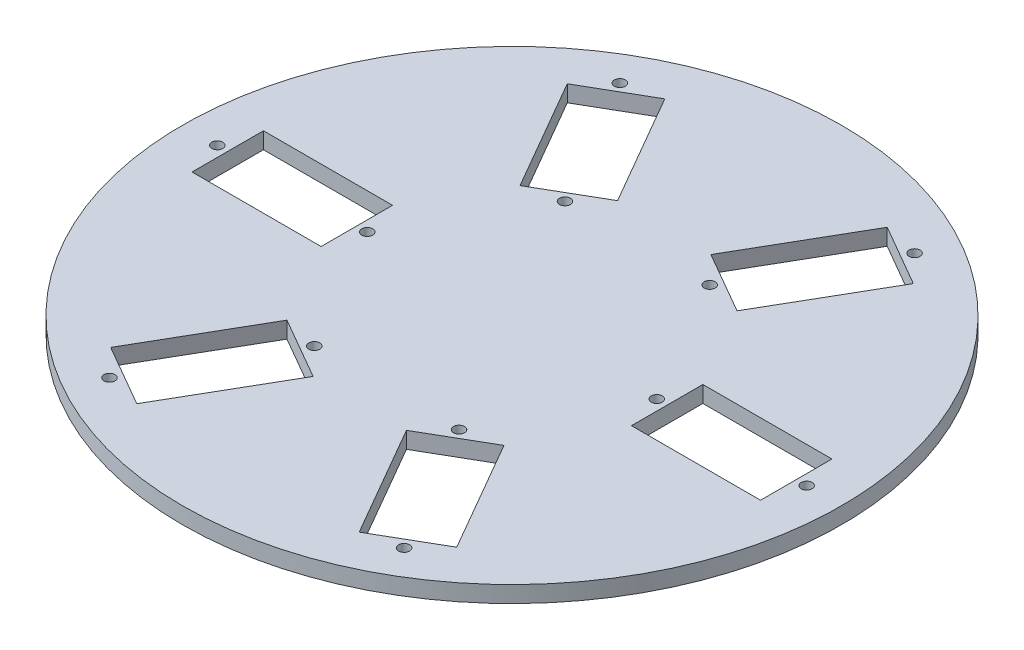
SolidWorks part; units mm, degrees
ref_plane "Спереди" through (0, 0, 0) normal (0, 0, 1) x (1, 0, 0)
ref_plane "Сверху" through (0, 0, 0) normal (0, 1, 0) x (1, 0, 0)
ref_plane "Справа" through (0, 0, 0) normal (1, 0, 0) x (0, 0, -1)
sketch "Sketch1" plane through (0, 0, 0) normal (0, 1, 0) x (1, 0, 0)
  line L0 (-60, 0) -> (60, 0) construction
  line L1 (28.25, -6.5) -> (28.25, 6.5)
  line L2 (28.25, 6.5) -> (51.75, 6.5)
  line L3 (51.75, 6.5) -> (51.75, -6.5)
  line L4 (28.25, -6.5) -> (51.75, -6.5)
  line L5 (40, -6.5) -> (40, 6.5) construction
  line L6 (0, 60) -> (0, -60) construction
  line L7 (28.25, 6.5) -> (28.25, -6.5)
  line L8 (51.75, -6.5) -> (51.75, 6.5)
  line L9 (8.4958, -27.7152) -> (19.7542, -21.2152)
  line L10 (19.7542, -21.2152) -> (31.5042, -41.5668)
  line L11 (31.5042, -41.5668) -> (20.2458, -48.0668)
  line L12 (8.4958, -27.7152) -> (20.2458, -48.0668)
  line L13 (19.7542, -21.2152) -> (8.4958, -27.7152)
  line L14 (20.2458, -48.0668) -> (31.5042, -41.5668)
  line L15 (14.3708, -37.891) -> (25.6292, -31.391) construction
  line L16 (-19.7542, -21.2152) -> (-8.4958, -27.7152)
  line L17 (-8.4958, -27.7152) -> (-20.2458, -48.0668)
  line L18 (-20.2458, -48.0668) -> (-31.5042, -41.5668)
  line L19 (-19.7542, -21.2152) -> (-31.5042, -41.5668)
  line L20 (-8.4958, -27.7152) -> (-19.7542, -21.2152)
  line L21 (-31.5042, -41.5668) -> (-20.2458, -48.0668)
  line L22 (-25.6292, -31.391) -> (-14.3708, -37.891) construction
  line L23 (-28.25, 6.5) -> (-28.25, -6.5)
  line L24 (-28.25, -6.5) -> (-51.75, -6.5)
  line L25 (-51.75, -6.5) -> (-51.75, 6.5)
  line L26 (-28.25, 6.5) -> (-51.75, 6.5)
  line L27 (-28.25, -6.5) -> (-28.25, 6.5)
  line L28 (-51.75, 6.5) -> (-51.75, -6.5)
  line L29 (-40, 6.5) -> (-40, -6.5) construction
  line L30 (-8.4958, 27.7152) -> (-19.7542, 21.2152)
  line L31 (-19.7542, 21.2152) -> (-31.5042, 41.5668)
  line L32 (-31.5042, 41.5668) -> (-20.2458, 48.0668)
  line L33 (-8.4958, 27.7152) -> (-20.2458, 48.0668)
  line L34 (-19.7542, 21.2152) -> (-8.4958, 27.7152)
  line L35 (-20.2458, 48.0668) -> (-31.5042, 41.5668)
  line L36 (-14.3708, 37.891) -> (-25.6292, 31.391) construction
  line L37 (19.7542, 21.2152) -> (8.4958, 27.7152)
  line L38 (8.4958, 27.7152) -> (20.2458, 48.0668)
  line L39 (20.2458, 48.0668) -> (31.5042, 41.5668)
  line L40 (19.7542, 21.2152) -> (31.5042, 41.5668)
  line L41 (8.4958, 27.7152) -> (19.7542, 21.2152)
  line L42 (31.5042, 41.5668) -> (20.2458, 48.0668)
  line L43 (25.6292, 31.391) -> (14.3708, 37.891) construction
  line L44 (0, 0) -> (26.35, 0) construction
  circle A0 centre (0, 0) radius 60
  circle A1 centre (26.35, 0) radius 1
  circle A2 centre (53.65, 0) radius 1
  circle A3 centre (53.65, 0) radius 1
  circle A4 centre (13.175, -22.8198) radius 1
  circle A5 centre (26.825, -46.4623) radius 1
  circle A6 centre (26.825, -46.4623) radius 1
  circle A7 centre (-13.175, -22.8198) radius 1
  circle A8 centre (-26.825, -46.4623) radius 1
  circle A9 centre (-26.825, -46.4623) radius 1
  circle A10 centre (-26.35, 0) radius 1
  circle A11 centre (-53.65, 0) radius 1
  circle A12 centre (-53.65, 0) radius 1
  circle A13 centre (-13.175, 22.8198) radius 1
  circle A14 centre (-26.825, 46.4623) radius 1
  circle A15 centre (-26.825, 46.4623) radius 1
  circle A16 centre (13.175, 22.8198) radius 1
  circle A17 centre (26.825, 46.4623) radius 1
  circle A18 centre (26.825, 46.4623) radius 1
  point P10 (51.75, 0)
  point P11 (28.25, 0)
  point P28 (25.875, -44.8168)
  point P29 (14.125, -24.4652)
  point P41 (-25.875, -44.8168)
  point P42 (-14.125, -24.4652)
  point P48 (0, 0)
  point P55 (-51.75, 0)
  point P56 (-28.25, 0)
  point P68 (-25.875, 44.8168)
  point P69 (-14.125, 24.4652)
  point P81 (25.875, 44.8168)
  point P82 (14.125, 24.4652)
  dimension "D1" = 120
  dimension "D6" = 2
  dimension "D2" = 23.5
  dimension "D3" = 13
  dimension "D4" = 40
  dimension "D5" = 27.3
  dimension "D8" = 26.35
  dimension "D7" = 6
extrude "Boss-Extrude1" add sketch "Sketch1" along normal blind 3
